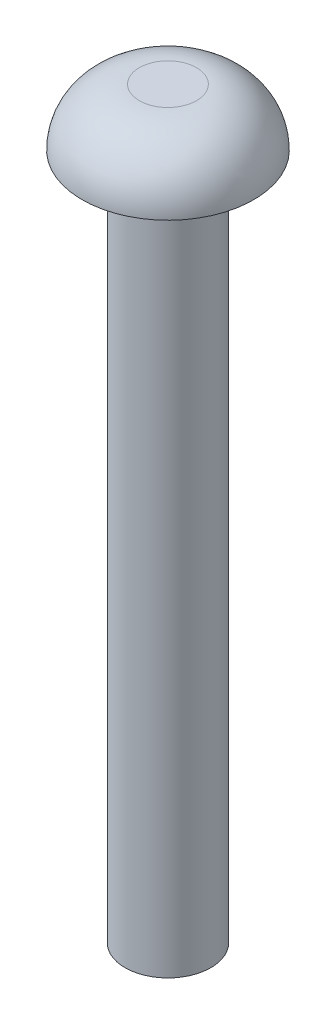
SolidWorks part; units mm, degrees
ref_plane "Front Plane" through (0, 0, 0) normal (0, 0, 1) x (1, 0, 0)
ref_plane "Top Plane" through (0, 0, 0) normal (0, 1, 0) x (1, 0, 0)
ref_plane "Right Plane" through (0, 0, 0) normal (1, 0, 0) x (0, 0, -1)
sketch "Sketch1" plane through (0, 0, 0) normal (0, 0, 1) x (1, 0, 0)
  line L0 (6, 0) -> (-6, 0)
  line L1 (0, 0) -> (6, 0)
  line L2 (0, 0) -> (0, -96)
  line L3 (0, -96) -> (6, -96)
  line L4 (6, 0) -> (6, -96)
  line L5 (6, 8) -> (2, 8)
  line L6 (6, 0) -> (6, 8)
  arc A0 (2, 8) -> (-6, 0) centre (2, 0) ccw
  dimension "D3" = 8
  dimension "D1" = 96
  dimension "D2" = 6
  dimension "D4" = 8
  dimension "D5" = 12
revolve "Revolve2" add sketch "Sketch1" angle 360 about L4
